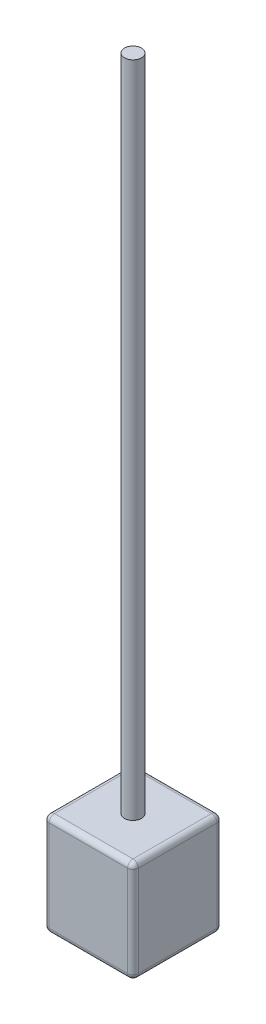
SolidWorks part; units mm, degrees
ref_plane "Front Plane" through (0, 0, 0) normal (0, 0, 1) x (1, 0, 0)
ref_plane "Top Plane" through (0, 0, 0) normal (0, 1, 0) x (1, 0, 0)
ref_plane "Right Plane" through (0, 0, 0) normal (1, 0, 0) x (0, 0, -1)
sketch "Sketch1" plane through (0, 0, 0) normal (0, 1, 0) x (1, 0, 0)
  line L1 (-21, -21) -> (21, -21)
  line L2 (-21, -21) -> (-21, 21)
  line L3 (-21, 21) -> (21, 21)
  line L4 (21, -21) -> (21, 21)
  line L5 (-21, -21) -> (21, 21) construction
  line L6 (-21, 21) -> (21, -21) construction
  point P0 (0, 0)
  dimension "D1" = 42
  dimension "D2" = 42
extrude "Boss-Extrude1" add sketch "Sketch1" along normal blind 48
sketch "Sketch2" plane through (0, 48, 0) normal (0, 1, 0) x (1, 0, 0)
  circle A0 centre (0, 0) radius 4
  dimension "D1" = 8
extrude "Boss-Extrude2" add sketch "Sketch2" along normal blind 310
fillet "Fillet1" radius 2.54 12 edges at (-21, 24, -21) (0, 0, -21) (-21, 0, 0) (21, 0, 0) (0, 0, 21) (-21, 24, 21) (21, 24, -21) (21, 24, 21) (-21, 48, 0) (0, 48, -21) (21, 48, 0) (0, 48, 21)
